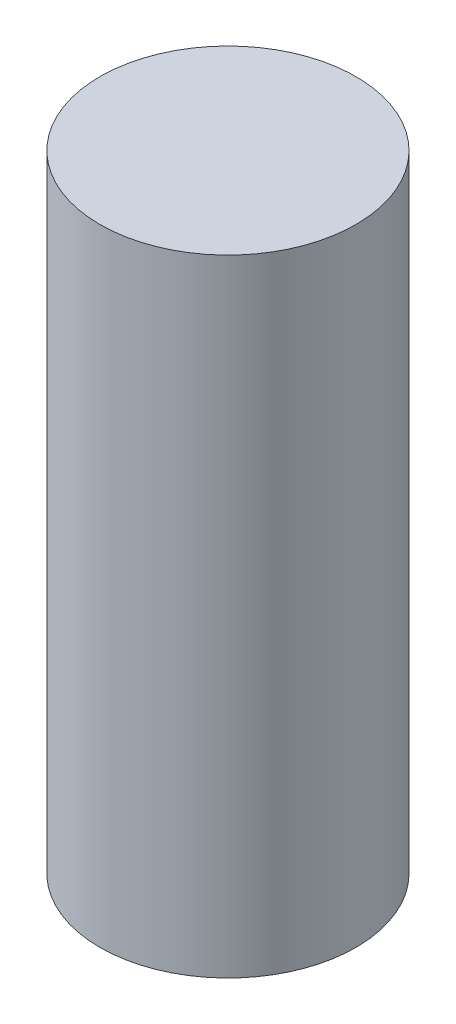
SolidWorks part; units mm, degrees
ref_plane "Front Plane" through (0, 0, 0) normal (0, 0, 1) x (1, 0, 0)
ref_plane "Top Plane" through (0, 0, 0) normal (0, 1, 0) x (1, 0, 0)
ref_plane "Right Plane" through (0, 0, 0) normal (1, 0, 0) x (0, 0, -1)
sketch "Sketch1" plane through (0, 0, 0) normal (0, 1, 0) x (1, 0, 0)
  circle A0 centre (0, 0) radius 13.5
  circle A1 centre (0, 0) radius 12.75
  dimension "D1" = 27
  dimension "D2" = 25.5
extrude "Boss-Extrude1" add sketch "Sketch1" along normal blind 64
sketch "Sketch2" plane through (0, 64, 0) normal (0, 1, 0) x (1, 0, 0)
  circle A0 centre (0, 0) radius 13.5
extrude "Boss-Extrude2" add sketch "Sketch2" along normal blind 2
